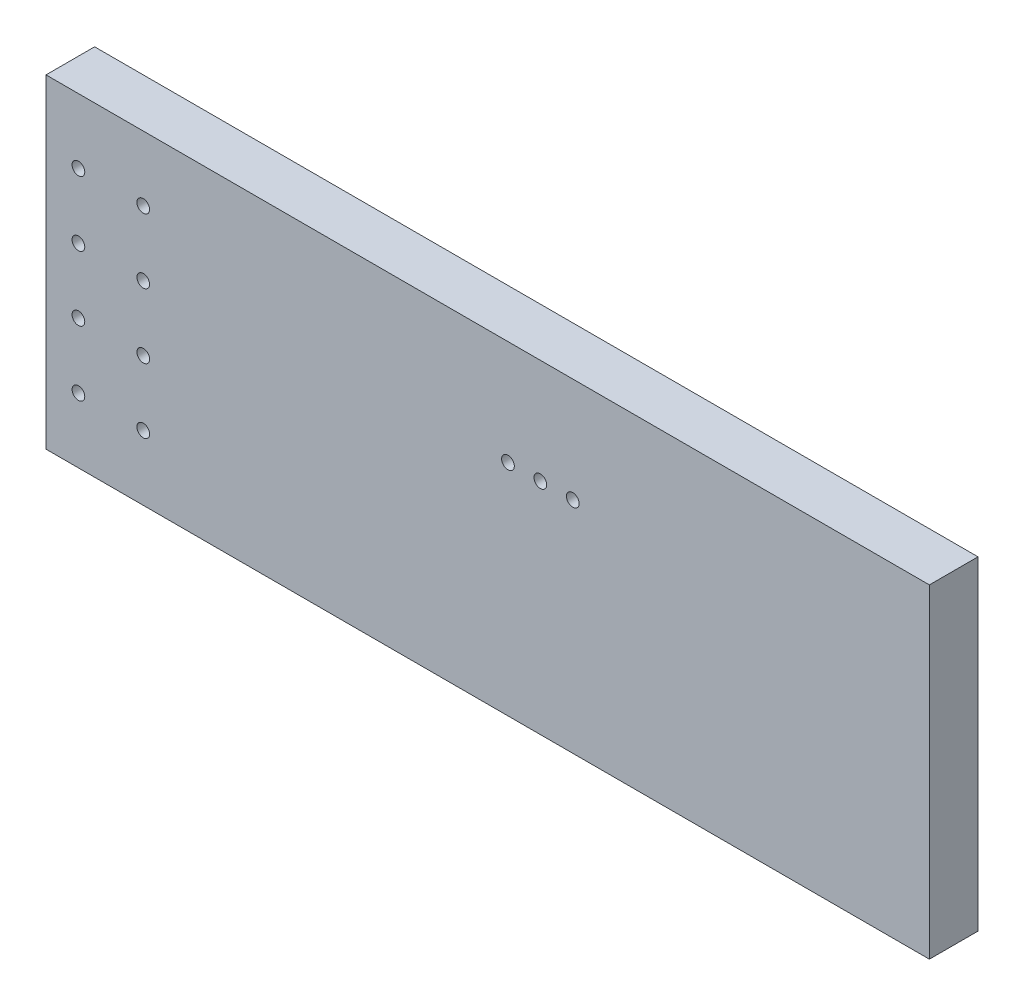
SolidWorks part; units mm, degrees
material "Pine"
ref_plane "Front Plane" through (0, 0, 0) normal (0, 0, 1) x (1, 0, 0)
ref_plane "Top Plane" through (0, 0, 0) normal (0, 1, 0) x (1, 0, 0)
ref_plane "Right Plane" through (0, 0, 0) normal (1, 0, 0) x (0, 0, -1)
sketch "Sketch1" plane through (0, 0, 0) normal (0, 0, 1) x (1, 0, 0)
  line L1 (0, 0) -> (717.55, 0)
  line L2 (0, 0) -> (0, 127)
  line L3 (0, 127) -> (717.55, 127)
  line L4 (717.55, 0) -> (717.55, 127)
  line L6 (717.55, 0) -> (717.55, 127)
  line L9 (0, 127) -> (-19.05, 127)
  line L10 (0, 127) -> (0, 0)
  line L11 (0, 0) -> (-19.05, 0)
  line L12 (-19.05, 127) -> (-19.05, 0)
  dimension "D1" = 717.55
  dimension "D2" = 127
  dimension "D3" = 19.05
extrude "Boss-Extrude1" add sketch "Sketch1" along normal blind 19.05 contours L1 L4 L3 L2
sketch "Sketch2" plane through (0, 0, 19.05) normal (0, 0, 1) x (1, 0, 0)
  line L3 (0, 0) -> (0, 127) construction
  line L4 (0, 127) -> (717.55, 127) construction
  line L5 (717.55, 0) -> (717.55, 127) construction
  circle A0 centre (12.7, 101.6) radius 2.4892
  circle A1 centre (38.1, 101.6) radius 2.4892
  circle A2 centre (38.1, 76.2) radius 2.4892
  circle A3 centre (38.1, 50.8) radius 2.4892
  circle A4 centre (38.1, 25.4) radius 2.4892
  circle A5 centre (12.7, 76.2) radius 2.4892
  circle A6 centre (12.7, 50.8) radius 2.4892
  circle A7 centre (12.7, 25.4) radius 2.4892
  circle A8 centre (685.8, 101.6) radius 2.4892
  circle A9 centre (660.4, 101.6) radius 2.4892
  circle A10 centre (660.4, 76.2) radius 2.4892
  circle A11 centre (660.4, 50.8) radius 2.4892
  circle A12 centre (660.4, 25.4) radius 2.4892
  circle A13 centre (685.8, 76.2) radius 2.4892
  circle A14 centre (685.8, 50.8) radius 2.4892
  circle A15 centre (685.8, 25.4) radius 2.4892
  dimension "D1" = 4.9784
  dimension "D2" = 25.4
  dimension "D3" = 12.7
  dimension "D6" = 25.4
  dimension "D7" = 31.75
  dimension "D8" = 4.9784
  dimension "D11" = 25.4
  dimension "D12" = 25.4
  dimension "D13" = 25.4
  dimension "D14" = 25.4
  dimension "D4" = 2
  dimension "D5" = 4
  dimension "D9" = 2
  dimension "D10" = 4
extrude "Cut-Extrude1" cut sketch "Sketch2" against normal blind 25.4
sketch "Sketch4" plane through (0, 0, 19.05) normal (0, 0, 1) x (1, 0, 0)
  line L0 (180.975, 85.979) -> (206.375, 85.979) construction
  line L1 (0, 127) -> (717.55, 127) construction
  line L2 (492.125, 85.979) -> (517.525, 85.979) construction
  line L3 (206.375, 85.979) -> (492.125, 85.979) construction
  line L4 (-19.05, 127) -> (717.55, 127) construction
  line L5 (-19.05, 127) -> (-19.05, 0) construction
  circle A0 centre (180.975, 85.979) radius 2.4892
  circle A1 centre (193.675, 85.979) radius 2.4892
  circle A2 centre (206.375, 85.979) radius 2.4892
  circle A3 centre (492.125, 85.979) radius 2.4892
  circle A4 centre (504.825, 85.979) radius 2.4892
  circle A5 centre (517.525, 85.979) radius 2.4892
  point P21 (349.25, 127)
  point P22 (349.25, 85.979)
  dimension "D1" = 4.9784
  dimension "D2" = 41.021
  dimension "D4" = 4.9784
  dimension "D6" = 41.021
  dimension "D7" = 285.75
  dimension "D3" = 12.7
  dimension "D5" = 12.7
extrude "Cut-Extrude2" cut sketch "Sketch4" against normal through all
sketch "Sketch5" plane through (0, 0, 19.05) normal (0, 0, 1) x (1, 0, 0)
  line L0 (0, 0) -> (717.55, 0) construction
  line L1 (717.55, 127) -> (346.075, 127)
  line L2 (717.55, 127) -> (717.55, 0)
  line L3 (717.55, 0) -> (346.075, 0)
  line L4 (346.075, 127) -> (346.075, 0)
  line L5 (-19.05, 127) -> (-19.05, 0) construction
  dimension "D1" = 365.125
extrude "Cut-Extrude3" cut sketch "Sketch5" against normal through all
